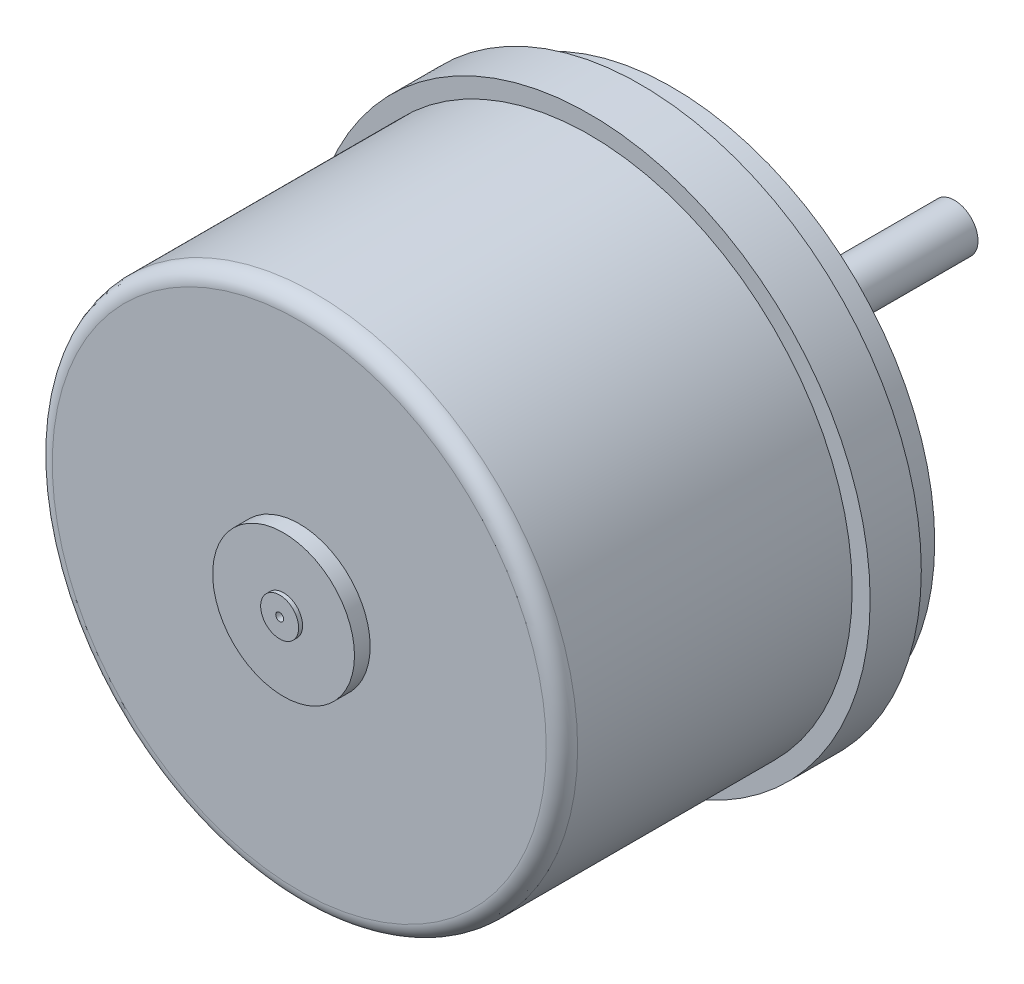
SolidWorks part; units mm, degrees
ref_plane "Alzado" through (0, 0, 0) normal (0, 0, 1) x (1, 0, 0)
ref_plane "Planta" through (0, 0, 0) normal (0, 1, 0) x (1, 0, 0)
ref_plane "Vista lateral" through (0, 0, 0) normal (1, 0, 0) x (0, 0, -1)
sketch "Croquis1" plane through (0, 0, 0) normal (0, 0, 1) x (1, 0, 0)
  circle A0 centre (0, 0) radius 33.485
  dimension "D1" = 66.97
extrude "Saliente-Extruir1" add sketch "Croquis1" along normal mid plane 4
sketch "Croquis2" plane through (0, 0, 2) normal (0, 0, 1) x (1, 0, 0)
  circle A0 centre (0, 0) radius 35.775
  dimension "D1" = 71.55
extrude "Saliente-Extruir2" add sketch "Croquis2" along normal blind 6.52
sketch "Croquis3" plane through (0, 0, 8.52) normal (0, 0, 1) x (1, 0, 0)
  circle A0 centre (0, 0) radius 33.485
  dimension "D1" = 66.97
extrude "Saliente-Extruir3" add sketch "Croquis3" along normal blind 37
sketch "Croquis4" plane through (0, 0, 45.52) normal (0, 0, 1) x (1, 0, 0)
  circle A0 centre (0, 0) radius 9.04
  dimension "D1" = 18.08
extrude "Saliente-Extruir4" add sketch "Croquis4" along normal blind 2
sketch "Croquis5" plane through (0, 0, 47.52) normal (0, 0, 1) x (1, 0, 0)
  circle A0 centre (0, 0) radius 2.425
  dimension "D1" = 4.85
extrude "Saliente-Extruir5" add sketch "Croquis5" along normal blind 0.5
sketch "Croquis6" plane through (0, 0, 48.02) normal (0, 0, 1) x (1, 0, 0)
  circle A0 centre (0, 0) radius 0.5
  dimension "D1" = 1
extrude "Cortar-Extruir1" cut sketch "Croquis6" against normal blind 1
sketch "Croquis7" plane through (0, 0, -2) normal (0, 0, -1) x (-1, 0, 0)
  circle A0 centre (0, 0) radius 3
  dimension "D1" = 6
extrude "Saliente-Extruir6" add sketch "Croquis7" along normal blind 36
fillet "Redondeo2" radius 2 1 edges at (33.485, 0, 45.52)
